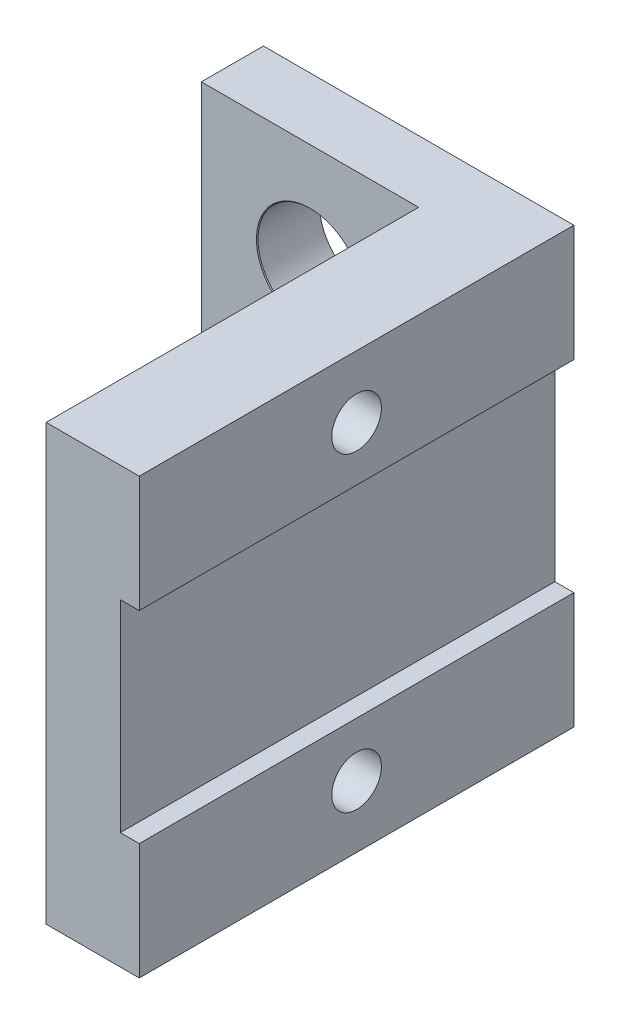
SolidWorks part; units mm, degrees
ref_plane "Front Plane" through (0, 0, 0) normal (0, 0, 1) x (1, 0, 0)
ref_plane "Top Plane" through (0, 0, 0) normal (0, 1, 0) x (1, 0, 0)
ref_plane "Right Plane" through (0, 0, 0) normal (1, 0, 0) x (0, 0, -1)
sketch "Sketch1" plane through (0, 0, 0) normal (0, 1, 0) x (1, 0, 0)
  line L0 (-10, 0) -> (0, 0)
  line L1 (0, 0) -> (0, -14)
  line L2 (0, -14) -> (-3, -14)
  line L3 (-3, -14) -> (-3, -2)
  line L4 (-3, -2) -> (-10, -2)
  line L5 (-10, -2) -> (-10, 0)
  dimension "D1" = 2
  dimension "D2" = 10
  dimension "D3" = 3
  dimension "D4" = 14
extrude "Boss-Extrude1" add sketch "Sketch1" along normal blind 14
hole_wizard "M3 Clearance Hole1" positions "Sketch4" profile "Sketch3" hole size "M3" standard "ISO" end condition through all
sketch "Sketch4" plane through (0, 0, 2) normal (0, 0, 1) x (1, 0, 0)
  line L0 (-6.5, 14) -> (-6.5, 7) construction
  line L1 (-10, 14) -> (-3, 14) construction
  line L4 (-10, 7) -> (-3, 7) construction
  line L5 (-10, 14) -> (-10, 0) construction
  line L6 (-3, 14) -> (-3, 0) construction
  point P0 (-6.5, 10.5)
  point P22 (-6.5, 3.5)
  point P26 (-6.5, 10.5)
sketch "Sketch3" plane through (-6.5, 10.5, 2) normal (1, 0, 0) x (0, -1, 0)
  line L0 (0, 0) -> (0, 2)
  line L1 (0, 2) -> (1.7, 2)
  line L2 (1.7, 2) -> (1.7, 0.025)
  line L3 (1.7, 0.025) -> (1.725, 0)
  line L5 (1.725, 0) -> (0, 0)
  line L6 (-1.7, 0.025) -> (-1.725, 0) construction
  line L11 (0, -6.35) -> (0, 107.95) construction
  dimension "Thru Hole Dia." = 3.4
  dimension "Thru Hole Depth" = 2
  dimension "Near C'Sink Dia." = 3.45
  dimension "Near C'Sink Angle" = 90
sketch "Sketch2" plane through (0, 0, 14) normal (0, 0, 1) x (1, 0, 0)
  line L0 (0, 14) -> (0, 0) construction
  line L1 (0, 10.25) -> (-0.61, 10.25)
  line L2 (0, 10.25) -> (0, 3.75)
  line L3 (0, 3.75) -> (-0.61, 3.75)
  line L4 (-0.61, 10.25) -> (-0.61, 3.75)
  point P6 (0, 7)
  point P7 (0, 7)
  dimension "D1" = 6.5
  dimension "D2" = 0.61
extrude "Cut-Extrude1" cut sketch "Sketch2" against normal through all
hole_wizard "M2 Tapped Hole1" positions "Sketch9" profile "Sketch10" tap size "M2" standard "ISO" end condition through all
sketch "Sketch9" plane through (0, 5.8588, -1.1586) normal (-1, 0, 0) x (0, 0, 1)
  line L0 (8.1586, 8.1412) -> (8.1586, -5.8588) construction
  line L1 (3.1586, 8.1412) -> (15.1586, 8.1412) construction
  line L4 (15.1586, 1.1412) -> (1.1586, 1.1412) construction
  line L5 (15.1586, 8.1412) -> (15.1586, -5.8588) construction
  line L8 (15.1586, 8.1412) -> (1.1586, 8.1412) construction
  point P0 (8.1586, 6.1412)
  point P21 (8.1586, -3.8588)
  point P29 (8.1586, 8.1412)
  dimension "D1" = 2
sketch "Sketch10" plane through (0, 12, 7) normal (0, 1, 0) x (0, 0, -1)
  line L0 (0, 0) -> (0, 10)
  line L1 (0, 10) -> (0.8, 10)
  line L2 (0.8, 10) -> (0.8, 0)
  line L5 (0.8, 0) -> (0, 0)
  line L11 (0, -6.35) -> (0, 107.95) construction
  dimension "Thru Tap Drill Dia." = 1.6
  dimension "Thru Tap Drill Depth" = 10
cosmetic thread "Hole Thread3"
cosmetic thread "Hole Thread4"
